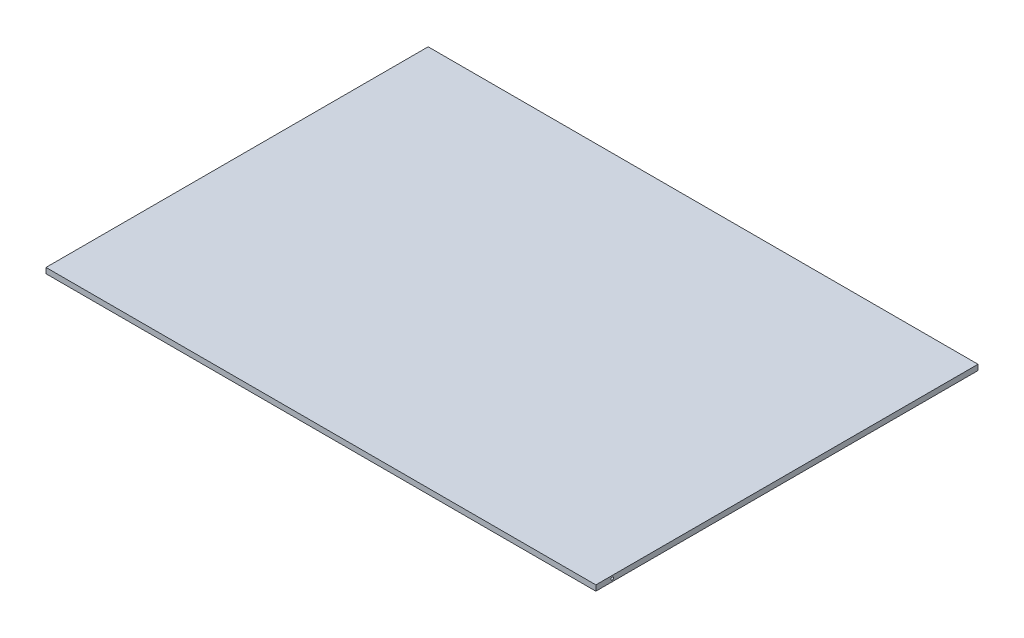
SolidWorks part; units mm, degrees
ref_plane "Front Plane" through (0, 0, 0) normal (0, 0, 1) x (1, 0, 0)
ref_plane "Top Plane" through (0, 0, 0) normal (0, 1, 0) x (1, 0, 0)
ref_plane "Right Plane" through (0, 0, 0) normal (1, 0, 0) x (0, 0, -1)
sketch "Sketch1" plane through (0, 0, 0) normal (0, 1, 0) x (1, 0, 0)
  line L1 (100, -67) -> (-100, -67)
  line L2 (100, -67) -> (100, 67)
  line L3 (100, 67) -> (-100, 67)
  line L4 (-100, -67) -> (-100, 67)
  line L5 (100, -67) -> (-100, 67) construction
  line L6 (100, 67) -> (-100, -67) construction
  point P0 (0, 0)
  dimension "D1" = 200
  dimension "D2" = 134
extrude "Boss-Extrude1" add sketch "Sketch1" along normal blind 2
sketch "Sketch2" plane through (100, 0, 0) normal (1, 0, 0) x (0, 0, -1)
  line L0 (-67, 2) -> (-67, 0) construction
  circle A0 centre (-66, 1) radius 0.5
  dimension "D2" = 1
  dimension "D1" = 1
extrude "Cut-Extrude1" cut sketch "Sketch2" against normal through all
sketch "Sketch3" plane through (0, 0, 67) normal (0, 0, 1) x (1, 0, 0)
  line L1 (-100, 0) -> (100, 0)
  line L2 (-100, 0) -> (-100, 2)
  line L3 (-100, 2) -> (100, 2)
  line L4 (100, 0) -> (100, 2)
extrude "Boss-Extrude2" add sketch "Sketch3" along normal blind 5
